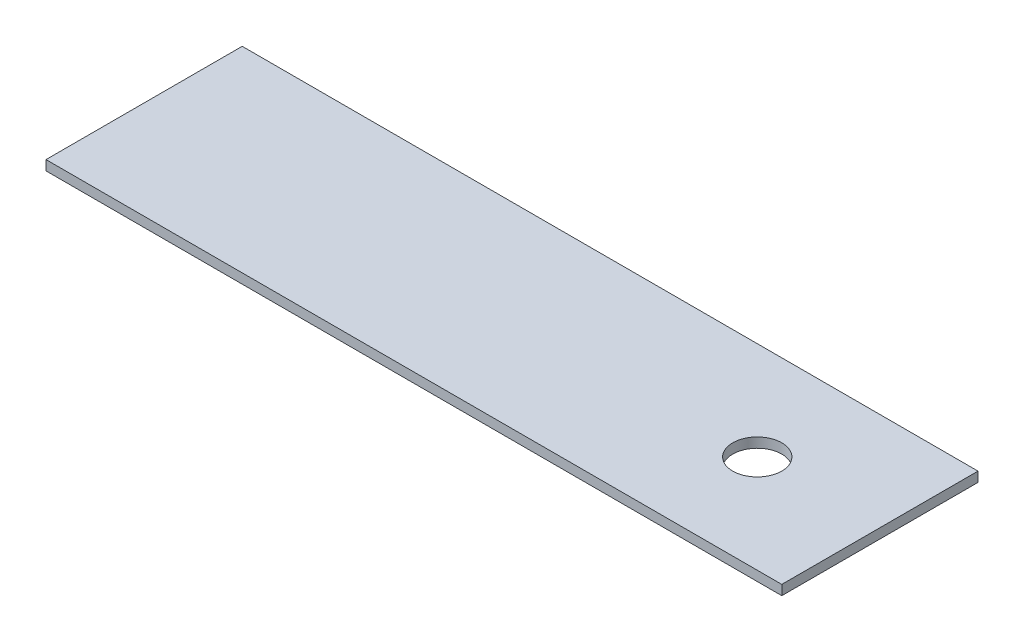
SolidWorks part; units mm, degrees
ref_plane "前视基准面" through (0, 0, 0) normal (0, 0, 1) x (1, 0, 0)
ref_plane "上视基准面" through (0, 0, 0) normal (0, 1, 0) x (1, 0, 0)
ref_plane "右视基准面" through (0, 0, 0) normal (1, 0, 0) x (0, 0, -1)
sketch "草图1" plane through (0, 0, 0) normal (0, 1, 0) x (1, 0, 0)
  line L1 (-33.2856, 10.1796) -> (116.7144, 10.1796)
  line L2 (-33.2856, 10.1796) -> (-33.2856, -29.8204)
  line L3 (-33.2856, -29.8204) -> (116.7144, -29.8204)
  line L4 (116.7144, 10.1796) -> (116.7144, -29.8204)
  dimension "D1" = 150
  dimension "D2" = 40
extrude "凸台-拉伸1" add sketch "草图1" along normal blind 2
sketch "草图2" plane through (0, 0, 0) normal (0, 1, 0) x (1, 0, 0)
  line L0 (-33.2856, -29.8204) -> (116.7144, -29.8204) construction
  line L1 (116.7144, -29.8204) -> (116.7144, 10.1796) construction
  circle A0 centre (91.7144, -9.8204) radius 5
  dimension "D1" = 20
  dimension "D2" = 25
extrude "切除-拉伸1" cut sketch "草图2" along normal through all
